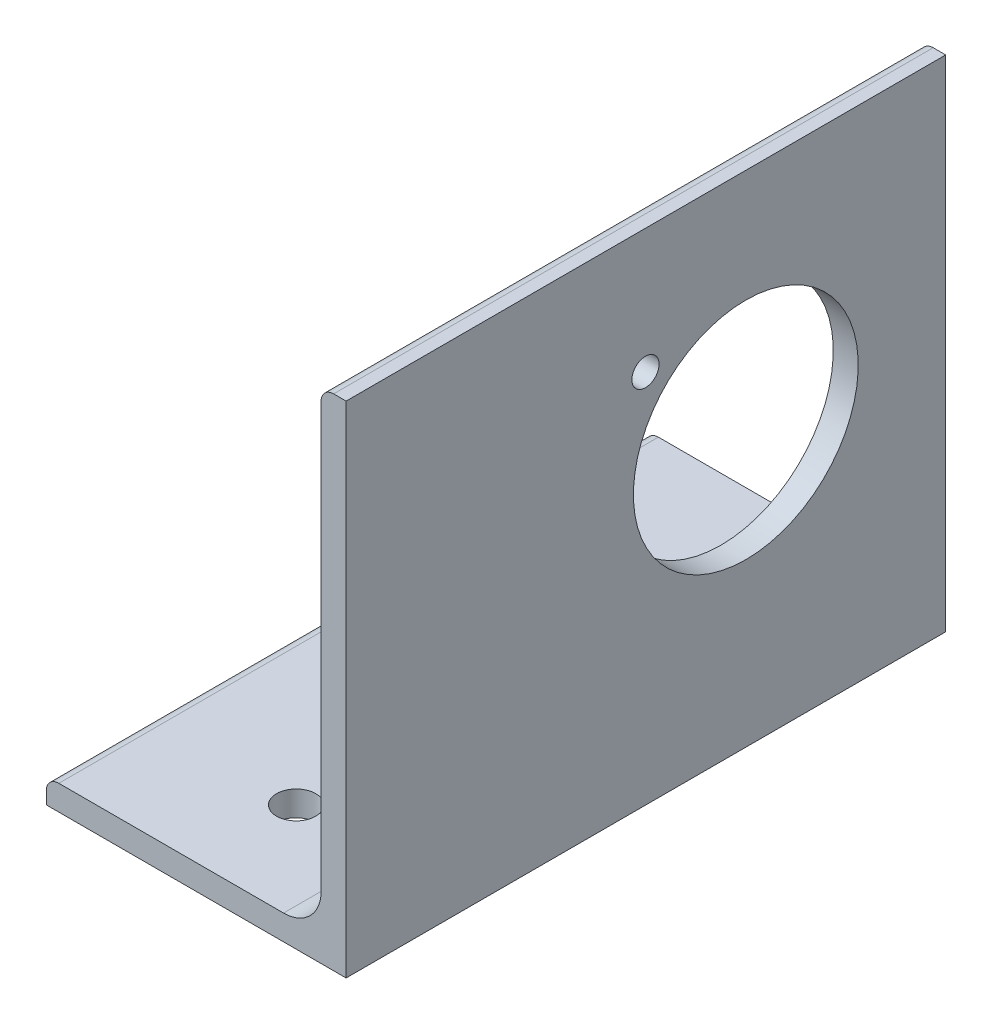
SolidWorks part; units mm, degrees
ref_plane "Front Plane" through (0, 0, 0) normal (0, 0, 1) x (1, 0, 0)
ref_plane "Top Plane" through (0, 0, 0) normal (0, 1, 0) x (1, 0, 0)
ref_plane "Right Plane" through (0, 0, 0) normal (1, 0, 0) x (0, 0, -1)
sketch "Sketch0" plane through (0, 0, 0) normal (0, 0, 1) x (1, 0, 0)
  line L0 (-19.05, -31.75) -> (19.05, -31.75)
  line L1 (19.05, -31.75) -> (19.05, 31.75)
  line L2 (19.05, 0) -> (0, 0) construction
  line L3 (0, 0) -> (0, -31.75) construction
  line L4 (15.875, -23.7998) -> (15.875, 31.75) construction
  line L5 (11.0998, -28.575) -> (-19.05, -28.575) construction
  arc A0 (15.875, -23.7998) -> (11.0998, -28.575) centre (11.0998, -23.7998) cw
  point P3 (14.4764, -27.1764)
  dimension "Inside Corner Radius" = 4.7752
  dimension "Outside Height" = 63.5
  dimension "Inside Height" = 60.325
  dimension "Inside Width" = 34.925
  dimension "Wall Thickness" = 3.175
  dimension "D1" = 3.175
  dimension "Outside Width" = 38.1
sketch "Sketch1" plane through (0, 0, 0) normal (1, 0, 0) x (0, 0, -1)
  line L0 (38.1, 0) -> (-38.1, 0)
  point P4 (0, 0)
  dimension "Length" = 76.2
sketch "Sketch2" plane through (0, 0, 0) normal (0, 0, 1) x (1, 0, 0)
  line L0 (-19.05, -31.75) -> (19.05, -31.75)
  line L1 (19.05, -31.75) -> (19.05, 31.75)
  line L2 (19.05, 31.75) -> (15.875, 31.75) construction
  line L3 (15.875, 30.1625) -> (15.875, -23.7998)
  line L4 (11.0998, -28.575) -> (-17.4625, -28.575)
  line L5 (-19.05, -31.75) -> (-19.05, -28.575) construction
  line L6 (17.4625, 31.75) -> (19.05, 31.75)
  line L7 (-19.05, -30.1625) -> (-19.05, -31.75)
  line L8 (19.05, 0) -> (0, 0) construction
  line L9 (0, 0) -> (0, -31.75) construction
  arc A0 (15.875, 30.1625) -> (17.4625, 31.75) centre (17.4625, 30.1625) cw
  arc A1 (-19.05, -30.1625) -> (-17.4625, -28.575) centre (-17.4625, -30.1625) cw
  arc A2 (15.875, -23.7998) -> (11.0998, -28.575) centre (11.0998, -23.7998) cw
  dimension "Inside Radius" = 4.7752
  dimension "Height" = 63.5
  dimension "Width" = 38.1
  dimension "Thickness" = 3.175
extrude "Boss-Extrude1" add sketch "Sketch2" along normal mid plane 76.2
sketch "Break Locations" plane through (0, 0, 0) normal (1, 0, 0) x (0, 0, -1)
  line L0 (26.67, 0) -> (-26.67, 0)
  line L1 (-38.1, -31.75) -> (-38.1, 31.75) construction
  line L2 (38.1, -31.75) -> (38.1, 31.75) construction
  point P0 (15.875, 0)
  point P1 (-15.875, 0)
  point P10 (0, 0)
  point P11 (-26.67, 0)
  point P13 (26.67, 0)
  dimension "D1" = 53.975
  dimension "D2" = 53.975
  dimension "D3" = 64.77
sketch "Sketch3" plane through (15.875, 0, 0) normal (-1, 0, 0) x (0, 0, 1)
  line L0 (-12.7, 3.1782) -> (0.052, 15.9301) construction
  line L1 (-12.7, 3.1782) -> (-38.1, 3.1813) construction
  line L3 (-38.1, 30.1625) -> (-38.1, -23.7998) construction
  circle A0 centre (-12.7, 3.1782) radius 14.2875
  circle A1 centre (0.052, 15.9301) radius 1.7272
  dimension "D1" = 25.4
extrude "Cut-Extrude1" cut sketch "Sketch3" against normal through all
sketch "Sketch9" plane through (0, -31.75, 0) normal (0, -1, 0) x (1, 0, 0)
  line L0 (19.05, 12.7) -> (0, 12.7) construction
  line L2 (0, 12.7) -> (0, 25.4) construction
  line L3 (0, 12.7) -> (0, 0) construction
  circle A0 centre (0, 25.4) radius 2.4892
  circle A1 centre (0, 0) radius 2.4892
  point P2 (0, 0)
  dimension "D1" = 19.05
  dimension "D2" = 25.4
  dimension "D3" = 25.4
extrude "Cut-Extrude2" cut sketch "Sketch9" against normal through all
equation "\"D1@Break Locations\" = .85 * \"Height@Sketch2\""
equation "\"D2@Break Locations\"=\"D1@Break Locations\""
equation "\"Thickness@Sketch2\"=\"wall thickness@sketch0\""
equation "\"Height@Sketch2\"=\"outside height@sketch0\""
equation "\"Width@Sketch2\"=\"outside width@sketch0\""
equation "\"Inside Radius@Sketch2\"=\"inside corner radius@sketch0\""
equation "\"Length@Boss-Extrude1\"=\"length@sketch1\""
equation "\"D3@Break Locations\"=\"D2@Break Locations\"*1.2"
equation "\"D1@Sketch0\"=\"Wall Thickness@Sketch0\""
